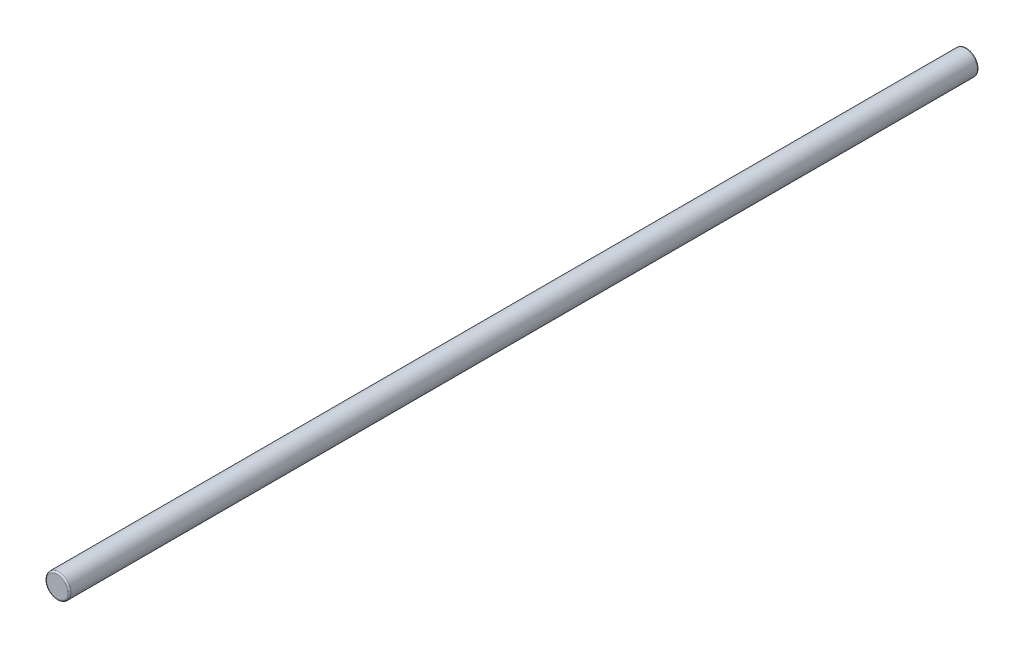
SolidWorks part; units mm, degrees
ref_plane "Alzado" through (0, 0, 0) normal (0, 0, 1) x (1, 0, 0)
ref_plane "Planta" through (0, 0, 0) normal (0, 1, 0) x (1, 0, 0)
ref_plane "Vista lateral" through (0, 0, 0) normal (1, 0, 0) x (0, 0, -1)
sketch "Croquis1" plane through (0, 0, 0) normal (0, 0, 1) x (1, 0, 0)
  circle A0 centre (0, 0) radius 4
  dimension "D1" = 8
extrude "Saliente-Extruir1" add sketch "Croquis1" along normal blind 300
fillet "Redondeo1" radius 0.5 2 edges at (4, 0, 0) (4, 0, 300)
